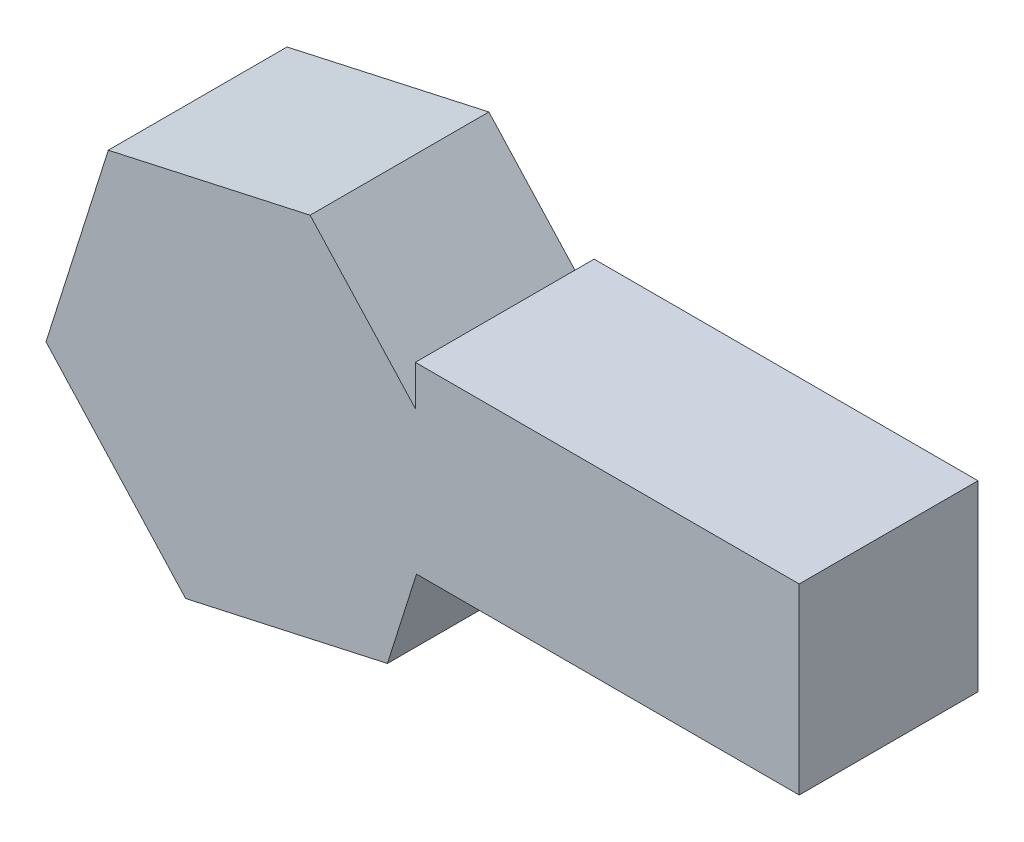
SolidWorks part; units mm, degrees
ref_plane "Front Plane" through (0, 0, 0) normal (0, 0, 1) x (1, 0, 0)
ref_plane "Top Plane" through (0, 0, 0) normal (0, 1, 0) x (1, 0, 0)
ref_plane "Right Plane" through (0, 0, 0) normal (1, 0, 0) x (0, 0, -1)
sketch "Sketch1" plane through (0, 0, 0) normal (0, 0, 1) x (1, 0, 0)
  line L1 (-114.884, 64.165) -> (151.2672, 64.165)
  line L2 (-114.884, 64.165) -> (-114.884, -62.5831)
  line L3 (-114.884, -62.5831) -> (151.2672, -62.5831)
  line L4 (151.2672, 64.165) -> (151.2672, -62.5831)
  line L5 (-91.0621, 10.3135) -> (-187.8313, 116.0377)
  line L6 (-187.8313, 116.0377) -> (-327.7757, 85.0952)
  line L7 (-327.7757, 85.0952) -> (-370.951, -51.5715)
  line L8 (-370.951, -51.5715) -> (-274.1818, -157.2957)
  line L9 (-274.1818, -157.2957) -> (-134.2373, -126.3532)
  line L10 (-134.2373, -126.3532) -> (-91.0621, 10.3135)
  circle A0 centre (-7.5507, 10.3135) radius 199.9589
  circle A1 centre (-231.0065, -20.629) radius 124.1226 construction
  point P7 (-91.0621, 10.3135)
extrude "Boss-Extrude1" add sketch "Sketch1" along normal blind 123.952 contours A0 L5 L6 L7 L8 L9 | L10 L3 L4 L1 L2 L5 | L3 L10 L5 L2 | L5 A0 L9 L10 L3 L2
